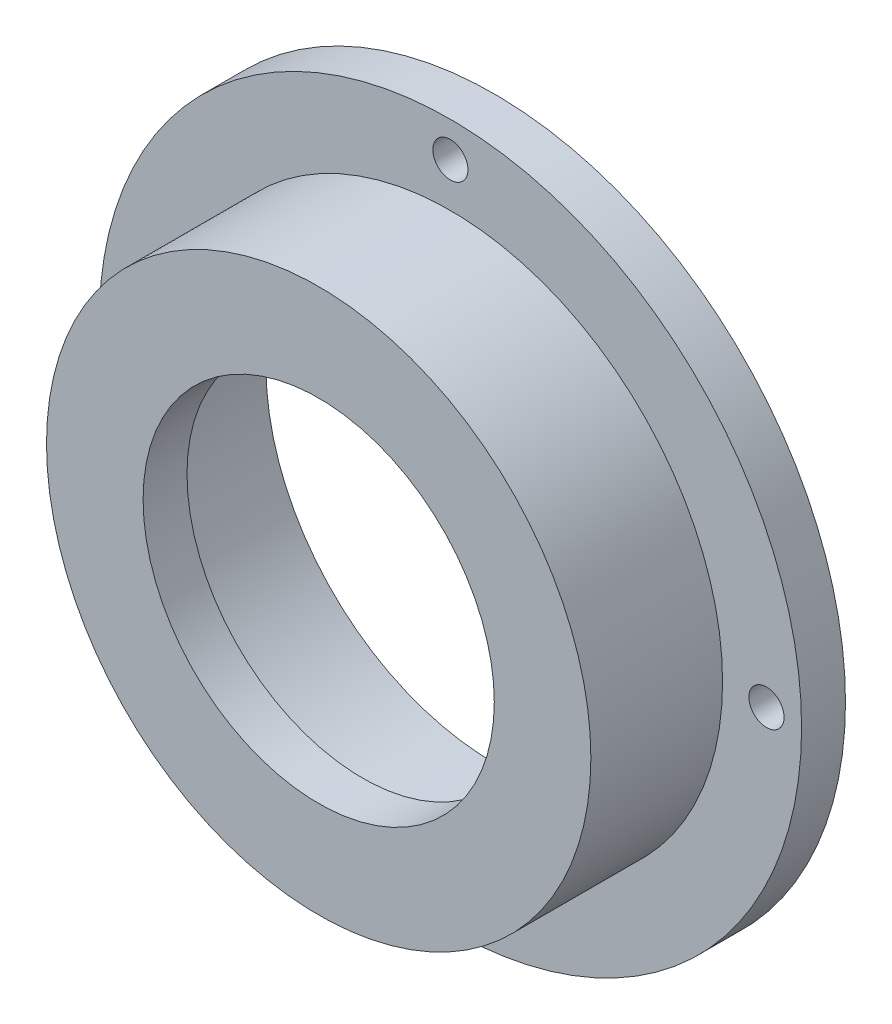
SolidWorks part; units mm, degrees
material "1060 合金"
ref_plane "前视基准面" through (0, 0, 0) normal (0, 0, 1) x (1, 0, 0)
ref_plane "上视基准面" through (0, 0, 0) normal (0, 1, 0) x (1, 0, 0)
ref_plane "右视基准面" through (0, 0, 0) normal (1, 0, 0) x (0, 0, -1)
sketch "草图1" plane through (0, 0, 0) normal (0, 0, 1) x (1, 0, 0)
  circle A0 centre (0, 0) radius 40
extrude "凸台-拉伸1" add sketch "草图1" along normal blind 5
sketch "草图2" plane through (0, 0, 5) normal (0, 0, 1) x (1, 0, 0)
  circle A0 centre (0, 0) radius 31
extrude "凸台-拉伸2" add sketch "草图2" along normal blind 12
sketch "草图3" plane through (0, 0, 0) normal (0, 0, -1) x (-1, 0, 0)
  circle A0 centre (0, 0) radius 26
extrude "切除-拉伸1" cut sketch "草图3" against normal blind 15
sketch "草图4" plane through (0, 0, 17) normal (0, 0, 1) x (1, 0, 0)
  circle A0 centre (0, 0) radius 31
extrude "凸台-拉伸3" add sketch "草图4" along normal blind 3
sketch "草图6" plane through (0, 0, 0) normal (0, 0, -1) x (-1, 0, 0)
  circle A0 centre (0, 36) radius 2
  point P0 (0, 0)
extrude "切除-拉伸3" cut sketch "草图6" against normal blind 5
pattern_circular "阵列(圆周)1" count 4 over 360 about axis through (0, 0, 0) along (0, 0, 1) of "切除-拉伸3"
sketch "草图7" plane through (0, 0, 20) normal (0, 0, 1) x (1, 0, 0)
  circle A0 centre (0, 0) radius 20
extrude "切除-拉伸4" cut sketch "草图7" against normal blind 10
